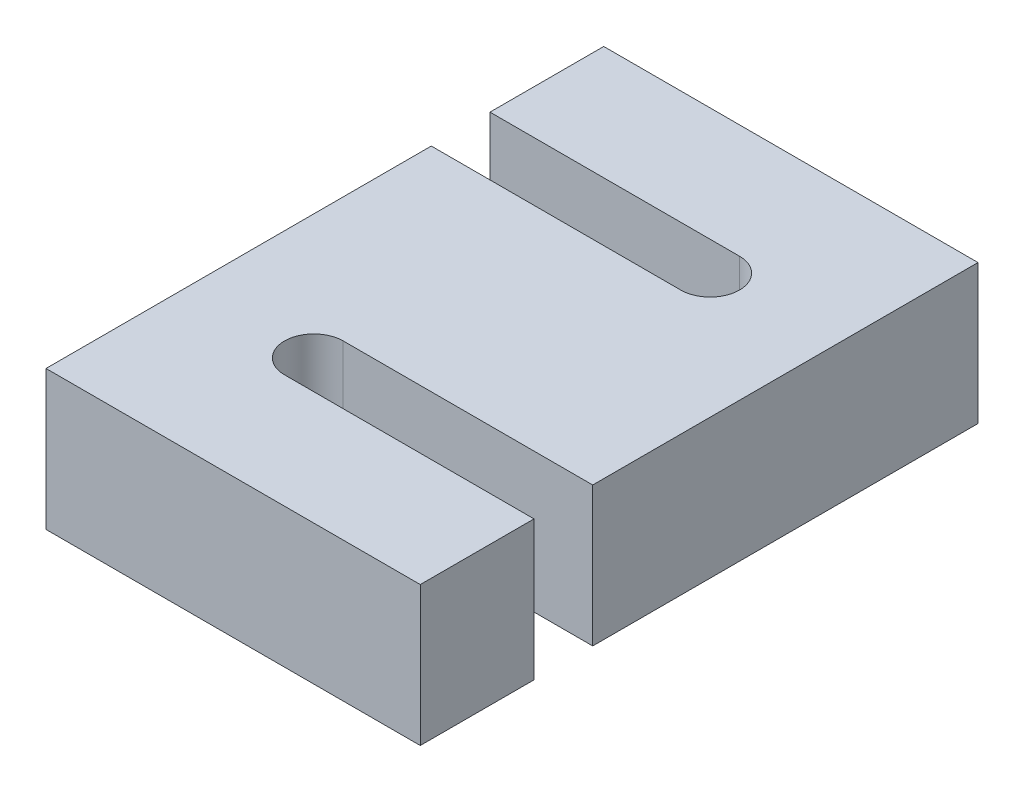
SolidWorks part; units mm, degrees
ref_plane "Front Plane" through (0, 0, 0) normal (0, 0, 1) x (1, 0, 0)
ref_plane "Top Plane" through (0, 0, 0) normal (0, 1, 0) x (1, 0, 0)
ref_plane "Right Plane" through (0, 0, 0) normal (1, 0, 0) x (0, 0, -1)
sketch "Sketch2" plane through (0, 0, 0) normal (0, 1, 0) x (1, 0, 0)
  line L0 (25.5, 0) -> (-8.5, 0)
  line L1 (25.5, 0) -> (25.5, 52.5)
  line L2 (25.5, 52.5) -> (-25.5, 52.5)
  line L3 (-25.5, 52.5) -> (-25.5, 37)
  line L4 (-25.5, 37) -> (8.5, 37)
  line L5 (8.5, 29) -> (-25.5, 29)
  line L6 (-25.5, 29) -> (-25.5, -23.5)
  line L7 (-25.5, -23.5) -> (25.5, -23.5)
  line L8 (25.5, -23.5) -> (25.5, -8)
  line L9 (-8.5, -8) -> (25.5, -8)
  arc A0 (8.5, 37) -> (8.5, 29) centre (8.5, 33) cw
  arc A1 (-8.5, 0) -> (-8.5, -8) centre (-8.5, -4) ccw
  point P4 (0, 0)
  dimension "D7" = 17
  dimension "D1" = 4
  dimension "D8" = 51
  dimension "D2" = 52.5
  dimension "D3" = 15.5
  dimension "D4" = 8
  dimension "D5" = 17
  dimension "D6" = 15.5
  dimension "D9" = 51
extrude "Boss-Extrude1" add sketch "Sketch2" along normal blind 19
